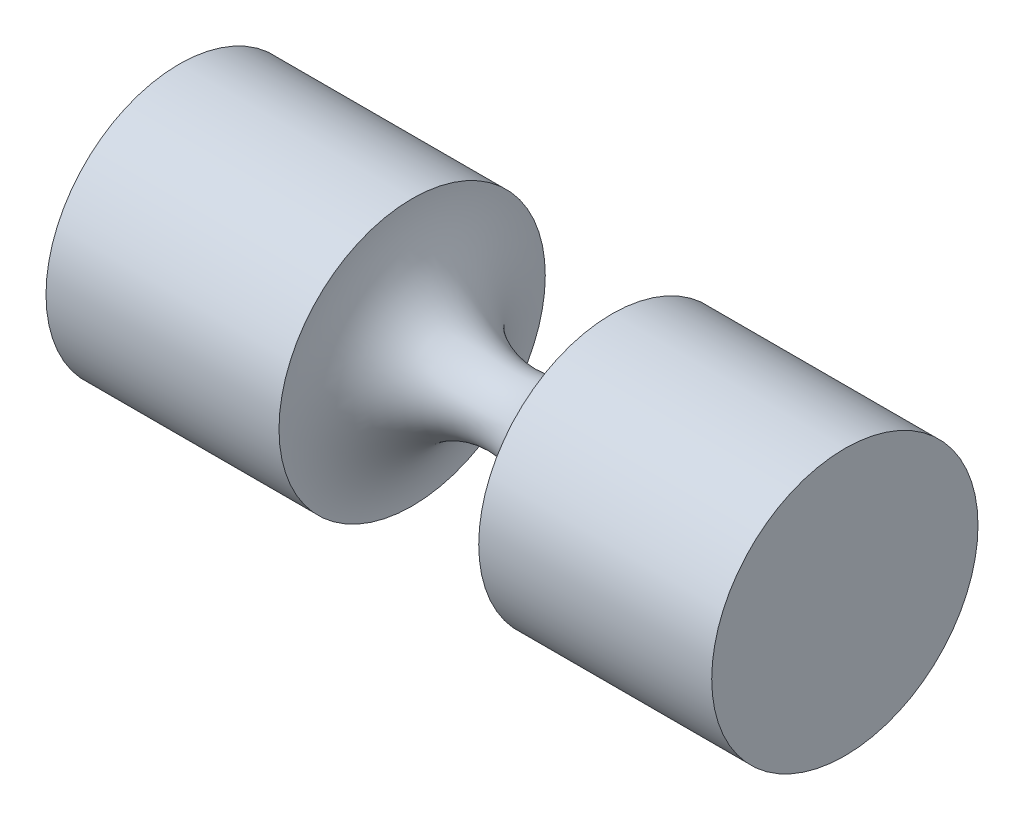
SolidWorks part; units mm, degrees
ref_plane "Front Plane" through (0, 0, 0) normal (0, 0, 1) x (1, 0, 0)
ref_plane "Top Plane" through (0, 0, 0) normal (0, 1, 0) x (1, 0, 0)
ref_plane "Right Plane" through (0, 0, 0) normal (1, 0, 0) x (0, 0, -1)
sketch "Sketch1" plane through (0, 0, 0) normal (0, 1, 0) x (1, 0, 0)
  line L0 (0, 0) -> (0, 20)
  line L2 (100, 20) -> (100, 0)
  line L3 (100, 0) -> (0, 0)
  line L4 (0, 20) -> (35, 20)
  line L5 (100, 20) -> (65, 20)
  arc A1 (35, 20) -> (65, 20) centre (50, 20) ccw
  point P8 (0, 0)
  point P9 (21.015, 26.4593)
  point P10 (65.4405, 24.7268)
  point P11 (52.8097, 21.8958)
  dimension "D3" = 35
  dimension "D4" = 20
  dimension "D5" = 20
  dimension "D1" = 100
  dimension "D2" = 35
revolve "Revolve1" add sketch "Sketch1" angle 360 about L3
scale "Scale3" scale about origin uniform scaling yes scale factor 2
